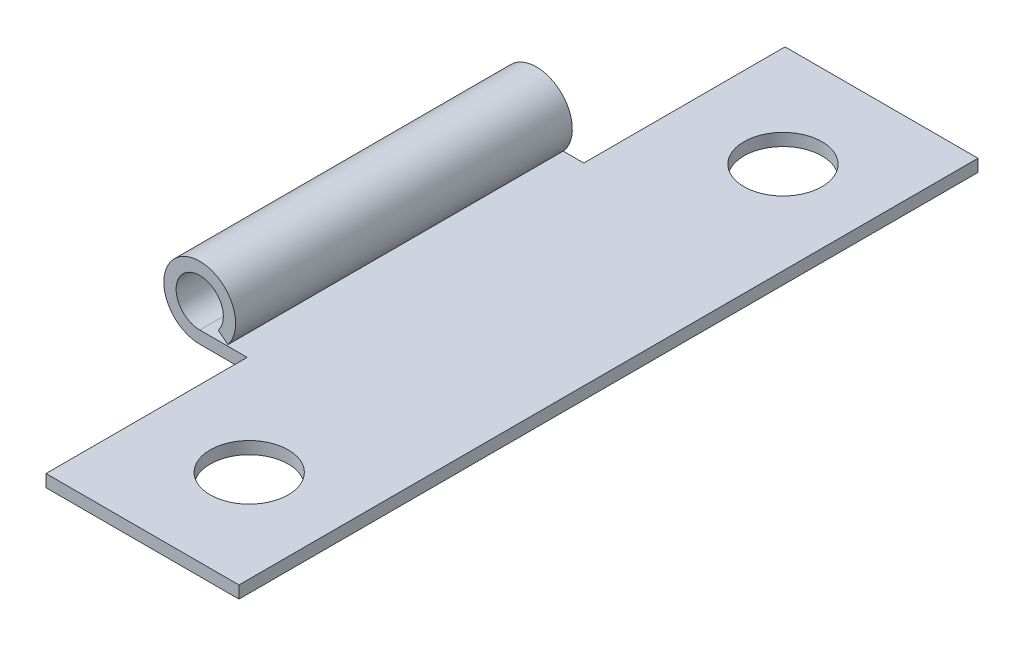
SolidWorks part; units mm, degrees
material "Latón"
ref_plane "Front" through (0, 0, 0) normal (0, 0, 1) x (1, 0, 0)
ref_plane "Top" through (0, 0, 0) normal (0, 1, 0) x (1, 0, 0)
ref_plane "Right" through (0, 0, 0) normal (1, 0, 0) x (0, 0, -1)
sketch "Sketch1" plane through (0, 0, 0) normal (0, 0, 1) x (1, 0, 0)
  line L0 (0, 0) -> (-13.4621, 0) construction
  line L1 (-13.4621, 0) -> (-13.4621, 5) construction
  line L2 (0, 0) -> (0, 0.6)
  line L3 (0, 0.6) -> (-11.7121, 0.6)
  line L4 (-11.7121, 0) -> (0, 0)
  line L5 (-10.8073, 1.0402) -> (-10.3352, 0.6699)
  circle A0 centre (-11.7121, 1.75) radius 1.75 construction
  arc A1 (-11.7121, 0) -> (-10.3352, 0.6699) centre (-11.7121, 1.75) cw
  circle A2 centre (-11.7121, 1.75) radius 1.15 construction
  arc A3 (-11.7121, 0.6) -> (-10.8073, 1.0402) centre (-11.7121, 1.75) cw
  dimension "D1" = 3.5
  dimension "D3" = 2.3
  dimension "D2" = 5
extrude "Boss-Extrude1" add sketch "Sketch1" along normal blind 36
sketch "Sketch2" plane through (0, 0.6, 0) normal (0, 1, 0) x (1, 0, 0)
  line L0 (-4.5, 0) -> (-4.5, -36) construction
  line L1 (0, 0) -> (-11.7121, 0) construction
  line L2 (0, -36) -> (-11.7121, -36) construction
  line L3 (0, -36) -> (0, 0) construction
  line L4 (0, -18) -> (-13.4621, -18) construction
  line L5 (-13.4621, 0) -> (-13.4621, -36) construction
  circle A0 centre (-4.5, -5) radius 1.9
  circle A1 centre (-4.5, -31) radius 1.9
  dimension "D2" = 3.8
  dimension "D1" = 4.5
  dimension "D3" = 5
extrude "Cut-Extrude1" cut sketch "Sketch2" against normal through all
sketch "Sketch3" plane through (0, 0.6, 0) normal (0, 1, 0) x (1, 0, 0)
  line L0 (-13.4621, 0) -> (-13.4621, -36) construction
  line L1 (-17.5243, -9.8) -> (-9.4, -9.8) construction
  line L2 (-17.5243, -9.8) -> (-17.5243, -26.2) construction
  line L3 (-17.5243, -26.2) -> (-9.4, -26.2) construction
  line L4 (-9.4, -9.8) -> (-9.4, -26.2) construction
  line L5 (-17.5243, -9.8) -> (-9.4, -26.2) construction
  line L6 (-17.5243, -26.2) -> (-9.4, -9.8) construction
  line L7 (0, -36) -> (0, 0) construction
  line L9 (-9.4, -9.8) -> (-16.1783, -9.8)
  line L10 (-9.4, -9.8) -> (-9.4, 1.0071)
  line L11 (-9.4, 1.0071) -> (-16.1783, 1.0071)
  line L12 (-16.1783, -9.8) -> (-16.1783, 1.0071)
  line L13 (-9.4, -26.2) -> (-18.2805, -26.2)
  line L14 (-9.4, -26.2) -> (-9.4, -36.9323)
  line L15 (-9.4, -36.9323) -> (-18.2805, -36.9323)
  line L16 (-18.2805, -26.2) -> (-18.2805, -36.9323)
  point P0 (-13.4621, -18)
  dimension "D1" = 16.4
  dimension "D2" = 9.4
  dimension "D3" = 10.8071
  dimension "D4" = 6.7783
  dimension "D5" = 10.7323
  dimension "D6" = 8.8805
extrude "Cut-Extrude2" cut sketch "Sketch3" against normal through all both and the other way through all
